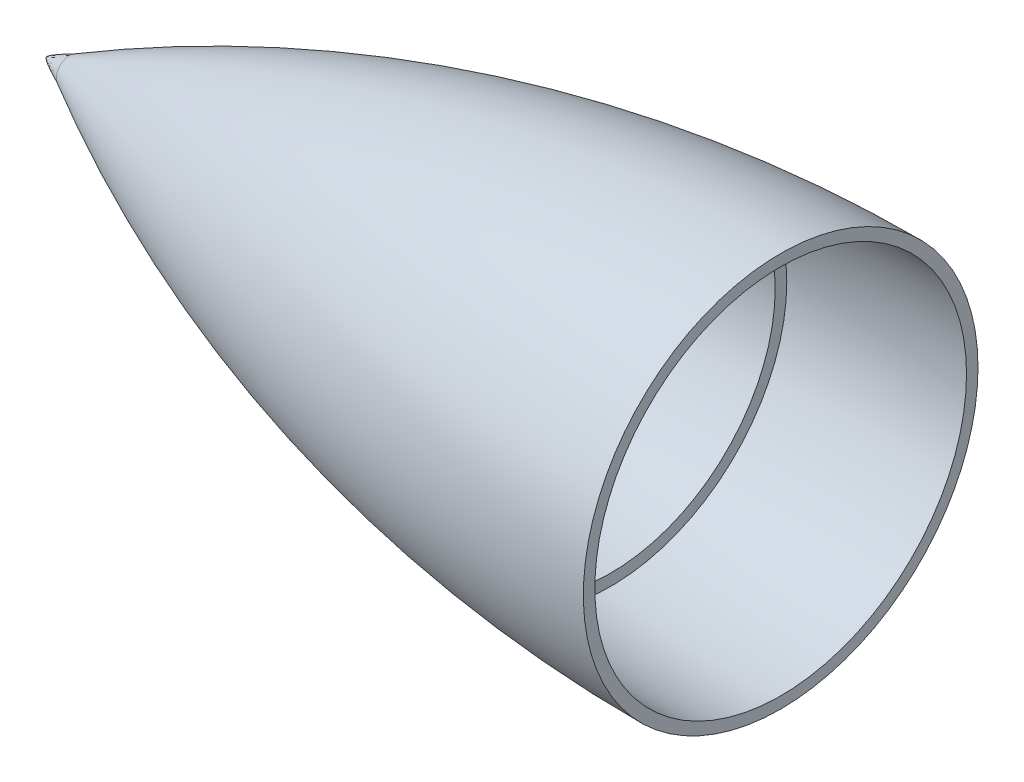
SolidWorks part; units mm, degrees
ref_plane "Front Plane" through (0, 0, 0) normal (0, 0, 1) x (1, 0, 0)
ref_plane "Top Plane" through (0, 0, 0) normal (0, 1, 0) x (1, 0, 0)
ref_plane "Right Plane" through (0, 0, 0) normal (1, 0, 0) x (0, 0, -1)
sketch "Sketch1" plane through (0, 0, 0) normal (0, 0, 1) x (1, 0, 0)
  line L0 (0, 0) -> (0, 314.1744) construction
  line L2 (0, 319.1744) -> (0, 316.6744)
  line L6 (81, 276.1744) -> (-149.7774, 276.1744) construction
  line L12 (-149.7774, 276.1744) -> (-37, 276.1744) construction
  line L13 (-37, 311.9881) -> (-37, 314.5055)
  line L14 (-5, 309.1744) -> (81, 309.1744) construction
  line L15 (-5, 314.1346) -> (-5, 309.1744) construction
  line L16 (0, 316.6744) -> (0, 319.1744) construction
  line L17 (0, 319.1744) -> (0, 314.1744) construction
  line L18 (0, 314.1744) -> (86, 314.1744) construction
  line L19 (81, 309.1744) -> (81, 276.1744) construction
  line L20 (86, 314.1744) -> (86, 276.1744) construction
  line L21 (-160, 276.1744) -> (-149.7774, 276.1744)
  arc A0 (0, 319.1744) -> (-160, 276.1744) centre (0, 0) ccw
  arc A1 (-37, 311.9881) -> (-149.7774, 276.1744) centre (0, 0) ccw
  arc A2 (-5, 314.1346) -> (-157.4935, 271.848) centre (0, 0) ccw construction
  arc A3 (-5.0398, 316.6343) -> (-37, 314.5055) centre (0, 0) ccw
  arc A6 (0, 316.6744) -> (-37, 314.5055) centre (0, 0) ccw
  arc A7 (-5, 314.1346) -> (-149.7774, 276.1744) centre (0, 0) ccw construction
  arc A9 (-5.0398, 316.6343) -> (-150.9692, 278.372) centre (0, 0) ccw construction
  dimension "D1" = 160
  dimension "D2" = 5
  dimension "D6" = 123
  dimension "D5" = 2.5
revolve "Revolve1" add sketch "Sketch1" angle 360 about L6
sketch "Sketch2" plane through (0, 0, 0) normal (0, 0, 1) x (1, 0, 0)
  line L0 (-155, 276.1744) -> (-155, 279.0113)
  line L1 (-160, 276.1744) -> (-155, 276.1744) construction
  line L2 (-160, 276.1744) -> (-155, 276.1744)
  arc A0 (0, 319.1744) -> (-160, 276.1744) centre (0, 0) ccw construction
  arc A2 (-155, 279.0113) -> (-160, 276.1744) centre (0, 0) ccw
  dimension "D1" = 5
revolve "Cut-Revolve1" cut sketch "Sketch2" angle 360 about L1
sketch "Sketch3" plane through (0, 0, 0) normal (0, 0, 1) x (1, 0, 0)
  line L0 (-155, 279.0113) -> (-155, 273.3375) construction
  line L1 (-155, 279.0113) -> (-155, 276.1744)
  line L2 (-155, 276.1744) -> (-160, 276.1744)
  spline S0 degree 2 poles (-155, 279.0113) (-160.0282, 276.6892) (-160, 276.1744) knots 0 0 0 0.5 0.5 0.5
  dimension "D1" = 5
revolve "Revolve2" add sketch "Sketch3" angle 360 about L2
